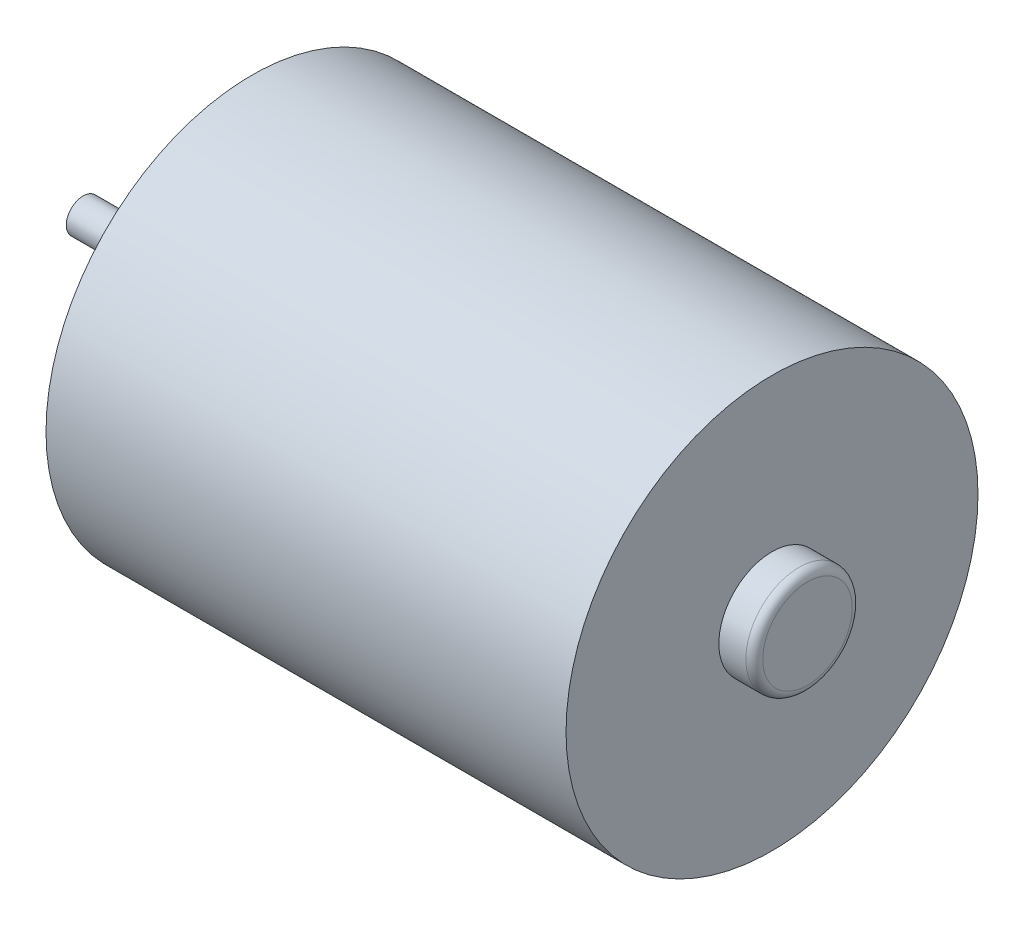
SolidWorks part; units mm, degrees
ref_plane "前视基准面" through (0, 0, 0) normal (0, 0, 1) x (1, 0, 0)
ref_plane "上视基准面" through (0, 0, 0) normal (0, 1, 0) x (1, 0, 0)
ref_plane "右视基准面" through (0, 0, 0) normal (1, 0, 0) x (0, 0, -1)
sketch "草图1" plane through (0, 0, 0) normal (1, 0, 0) x (0, 0, -1)
  circle A0 centre (0, 0) radius 12.2
  dimension "D1" = 24.4
extrude "凸台-拉伸1" add sketch "草图1" along normal blind 30.8
sketch "草图3" plane through (30.8, 0, 0) normal (1, 0, 0) x (0, 0, -1)
  circle A0 centre (0, 0) radius 3.15
  dimension "D1" = 6.3
extrude "凸台-拉伸2" add sketch "草图3" along normal blind 2.1
fillet "圆角1" radius 0.5 1 edges at (32.9, 0, -3.15)
sketch "草图4" plane through (0, 0, 0) normal (-1, 0, 0) x (0, 0, 1)
  circle A0 centre (0, 0) radius 3.225
  dimension "D1" = 6.45
extrude "凸台-拉伸3" add sketch "草图4" along normal blind 1.7
sketch "草图6" plane through (0, 0, 0) normal (-1, 0, 0) x (0, 0, 1)
  circle A0 centre (0, 0) radius 1
  dimension "D1" = 2
extrude "凸台-拉伸4" add sketch "草图6" along normal blind 10
sketch "草图7" plane through (0, 0, 0) normal (-1, 0, 0) x (0, 0, 1)
  line L0 (-8.5, 0) -> (8.5, 0) construction
  circle A0 centre (8.5, 0) radius 1.1
  circle A1 centre (-8.5, 0) radius 1.1
  point P5 (0, 0)
  dimension "D2" = 2.2
  dimension "D3" = 2.2
  dimension "D1" = 17
extrude "切除-拉伸2" cut sketch "草图7" against normal blind 3
